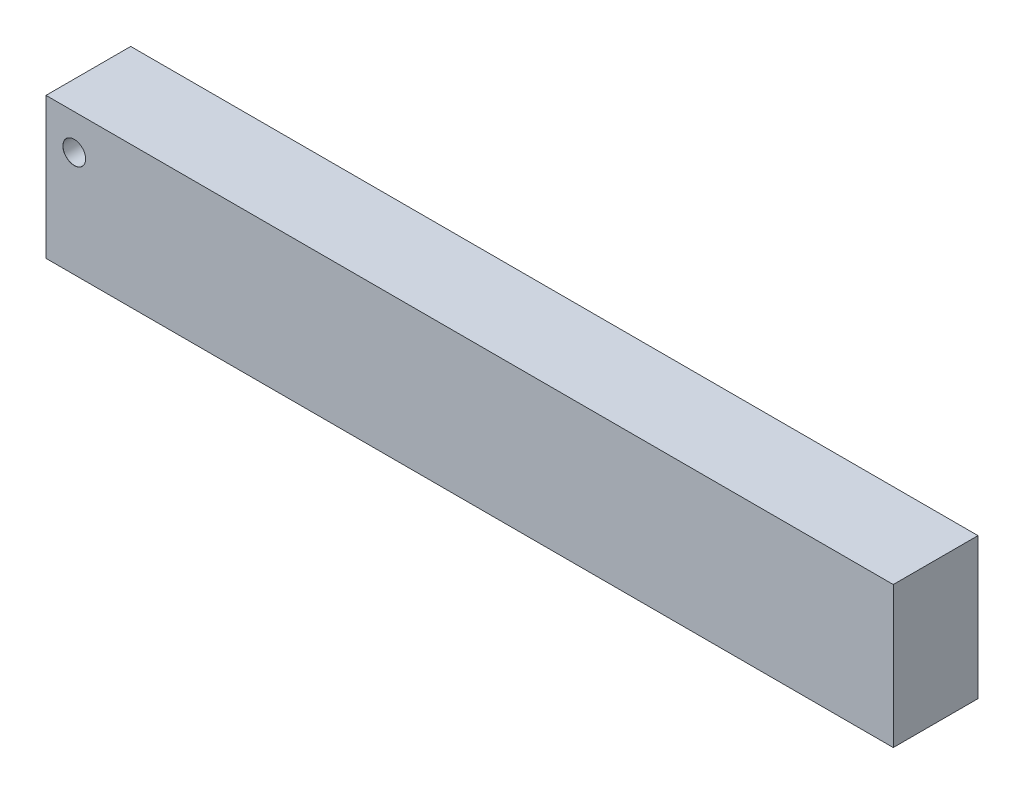
SolidWorks part; units mm, degrees
ref_plane "Front Plane" through (0, 0, 0) normal (0, 0, 1) x (1, 0, 0)
ref_plane "Top Plane" through (0, 0, 0) normal (0, 1, 0) x (1, 0, 0)
ref_plane "Right Plane" through (0, 0, 0) normal (1, 0, 0) x (0, 0, -1)
sketch "Sketch1" plane through (0, 0, 0) normal (0, 0, 1) x (1, 0, 0)
  line L1 (0, 0) -> (300, 0)
  line L2 (0, 0) -> (0, 50)
  line L3 (0, 50) -> (300, 50)
  line L4 (300, 0) -> (300, 50)
  dimension "D1" = 300
  dimension "D2" = 50
extrude "Boss-Extrude1" add sketch "Sketch1" along normal blind 30
hole_wizard "Ø8.0mm Dowel Hole1" positions "Sketch2" profile "Sketch3" hole size "Ø8.0" standard "ANSI Metric" end condition through all
sketch "Sketch2" plane through (0, 0, 30) normal (0, 0, 1) x (1, 0, 0)
  line L0 (0, 50) -> (0, 0) construction
  line L1 (300, 50) -> (0, 50) construction
  point P0 (10, 37.5)
  dimension "D1" = 10
  dimension "12.5" = 12.5
sketch "Sketch3" plane through (10, 37.5, 30) normal (1, 0, 0) x (0, -1, 0)
  line L0 (0, 0) -> (0, 30)
  line L1 (0, 30) -> (4, 30)
  line L2 (4, 30) -> (4, 0.025)
  line L3 (4, 0.025) -> (4.025, 0)
  line L5 (4.025, 0) -> (0, 0)
  line L6 (-4, 0.025) -> (-4.025, 0) construction
  line L11 (0, -6.35) -> (0, 107.95) construction
  dimension "Thru Hole Dia." = 8
  dimension "Thru Hole Depth" = 30
  dimension "Near C'Sink Dia." = 8.05
  dimension "Near C'Sink Angle" = 90
